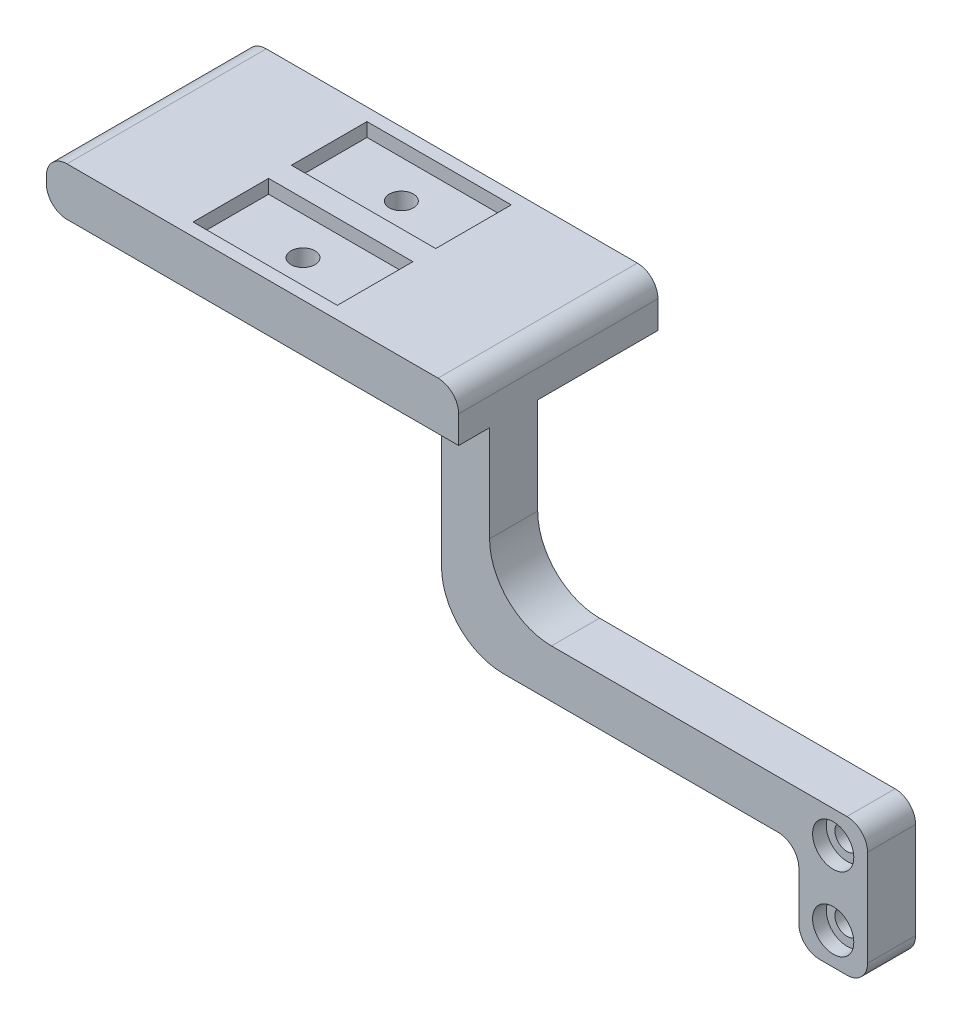
SolidWorks part; units mm, degrees
ref_plane "Ebene vorne" through (0, 0, 0) normal (0, 0, 1) x (1, 0, 0)
ref_plane "Ebene oben" through (0, 0, 0) normal (0, 1, 0) x (1, 0, 0)
ref_plane "Ebene rechts" through (0, 0, 0) normal (1, 0, 0) x (0, 0, -1)
sketch "Skizze1" plane through (0, 0, 0) normal (0, 0, 1) x (1, 0, 0)
  line L0 (0, 33.3884) -> (0, -30.3489) construction
  line L1 (-36.7599, 0) -> (60.9645, 0) construction
  line L2 (31, -13.5) -> (31, 0.5)
  line L3 (28, 3.5) -> (-15, 3.5)
  line L4 (-24, 12.5) -> (-24, 30.5)
  line L5 (-27, 33.5) -> (-81, 33.5)
  line L6 (-84, 30.5) -> (-84, 29.5)
  line L7 (-81, 26.5) -> (-36, 26.5)
  line L8 (-31, 21.5) -> (-31, 5.5)
  line L9 (-22, -3.5) -> (18, -3.5)
  line L10 (21, -6.5) -> (21, -13.5)
  line L11 (24, -16.5) -> (28, -16.5)
  line L12 (26, -29.7764) -> (26, 15.0957) construction
  line L13 (9.4668, -6.5) -> (36.9981, -6.5) construction
  circle A0 centre (26, -1.1504) radius 1.75
  circle A1 centre (26, -11.8496) radius 1.75
  arc A2 (-15, 3.5) -> (-24, 12.5) centre (-15, 12.5) cw
  arc A3 (-31, 5.5) -> (-22, -3.5) centre (-22, 5.5) ccw
  arc A4 (-36, 26.5) -> (-31, 21.5) centre (-36, 21.5) cw
  arc A5 (-81, 33.5) -> (-84, 30.5) centre (-81, 30.5) ccw
  arc A6 (-24, 30.5) -> (-27, 33.5) centre (-27, 30.5) ccw
  arc A7 (31, 0.5) -> (28, 3.5) centre (28, 0.5) ccw
  arc A8 (31, -13.5) -> (28, -16.5) centre (28, -13.5) cw
  arc A9 (21, -13.5) -> (24, -16.5) centre (24, -13.5) ccw
  arc A10 (18, -3.5) -> (21, -6.5) centre (18, -6.5) cw
  arc A11 (-84, 29.5) -> (-81, 26.5) centre (-81, 29.5) ccw
  point P33 (-84, 33.5)
  point P36 (-24, 33.5)
  point P39 (31, 3.5)
  point P42 (31, -16.5)
  point P49 (-84, 26.5)
  dimension "D9" = 3.5
  dimension "D10" = 3.5
  dimension "D11" = 9
  dimension "D12" = 9
  dimension "D13" = 5
  dimension "D14" = 3
  dimension "D15" = 3
  dimension "D1" = 10
  dimension "D2" = 20
  dimension "D3" = 60
  dimension "D4" = 30
  dimension "D5" = 7
  dimension "D6" = 7
  dimension "D7" = 45
  dimension "D8" = 7
extrude "Aufsatz-Linear austragen1" add sketch "Skizze1" along normal blind 29
ref_plane "Auflageebene" through (0, 0, 24.5) normal (0, 0, 1) x (1, 0, 0)
sketch "Skizze2" plane through (0, 0, 24.5) normal (0, 0, 1) x (1, 0, 0)
  line L0 (-81, 26.5) -> (-36, 26.5) construction
  line L1 (-50.9843, 26.5) -> (44.1932, 26.5)
  line L2 (-50.9843, 26.5) -> (-50.9843, -16.5)
  line L3 (-50.9843, -16.5) -> (44.1932, -16.5)
  line L4 (44.1932, 26.5) -> (44.1932, -16.5)
extrude "Schnitt-Linear austragen1" cut sketch "Skizze2" along normal blind 29
ref_plane "TiefeArm" through (0, 0, 17.5) normal (0, 0, 1) x (1, 0, 0)
sketch "Skizze5" plane through (0, 0, 17.5) normal (0, 0, 1) x (1, 0, 0)
  line L0 (-81, 26.5) -> (-24, 26.5) construction
  line L1 (-56.7896, 26.5) -> (45.589, 26.5)
  line L2 (-56.7896, 26.5) -> (-56.7896, -17.7623)
  line L3 (-56.7896, -17.7623) -> (45.589, -17.7623)
  line L4 (45.589, 26.5) -> (45.589, -17.7623)
extrude "Schnitt-Linear austragen2" cut sketch "Skizze5" against normal blind 29
sketch "Skizze6" plane through (0, 33.5, 0) normal (0, 1, 0) x (1, 0, 0)
  line L0 (-81, -14.5) -> (-27, -14.5) construction
  line L1 (-81, -29) -> (-81, 0) construction
  line L2 (-27, -29) -> (-27, 0) construction
  line L3 (-54, 0) -> (-54, -29) construction
  line L4 (-64.5, -1.8425) -> (-43.5, -1.8425)
  line L5 (-64.5, -1.8425) -> (-64.5, -12.8425)
  line L6 (-64.5, -12.8425) -> (-43.5, -12.8425)
  line L7 (-43.5, -1.8425) -> (-43.5, -12.8425)
  line L8 (-27, 0) -> (-81, 0) construction
  line L9 (-27, -29) -> (-81, -29) construction
  line L10 (-64.5, -7.3425) -> (-43.5, -7.3425) construction
  line L11 (-64.5, -16.1575) -> (-43.5, -16.1575)
  line L12 (-43.5, -27.1575) -> (-43.5, -16.1575)
  line L13 (-64.5, -27.1575) -> (-43.5, -27.1575)
  line L14 (-64.5, -27.1575) -> (-64.5, -16.1575)
  dimension "D1" = 21
  dimension "D2" = 11
extrude "Schnitt-Linear austragen3" cut sketch "Skizze6" against normal blind 2
sketch "Skizze7" plane through (0, 0, 24.5) normal (0, 0, 1) x (1, 0, 0)
  circle A0 centre (26, -1.1504) radius 3
  circle A1 centre (26, -11.8496) radius 3
  dimension "D1" = 6
  dimension "D2" = 6
extrude "Schnitt-Linear austragen4" cut sketch "Skizze7" against normal blind 2
sketch "Skizze8" plane through (0, 33.5, 0) normal (0, 1, 0) x (1, 0, 0)
  line L0 (-64.5, -7.3425) -> (-43.5, -7.3425) construction
  line L1 (-64.5, -1.8425) -> (-64.5, -12.8425) construction
  line L2 (-43.5, -12.8425) -> (-43.5, -1.8425) construction
  line L3 (-54, -1.8425) -> (-54, -12.8425) construction
  line L4 (-43.5, -1.8425) -> (-64.5, -1.8425) construction
  line L5 (-64.5, -12.8425) -> (-43.5, -12.8425) construction
  line L6 (-81, -14.5) -> (-27, -14.5) construction
  line L7 (-81, -29) -> (-81, 0) construction
  line L8 (-27, -29) -> (-27, 0) construction
  circle A0 centre (-54, -7.3425) radius 1.75
  circle A1 centre (-54, -21.6575) radius 1.75
  dimension "D1" = 3.5
extrude "Schnitt-Linear austragen5" cut sketch "Skizze8" against normal through all
